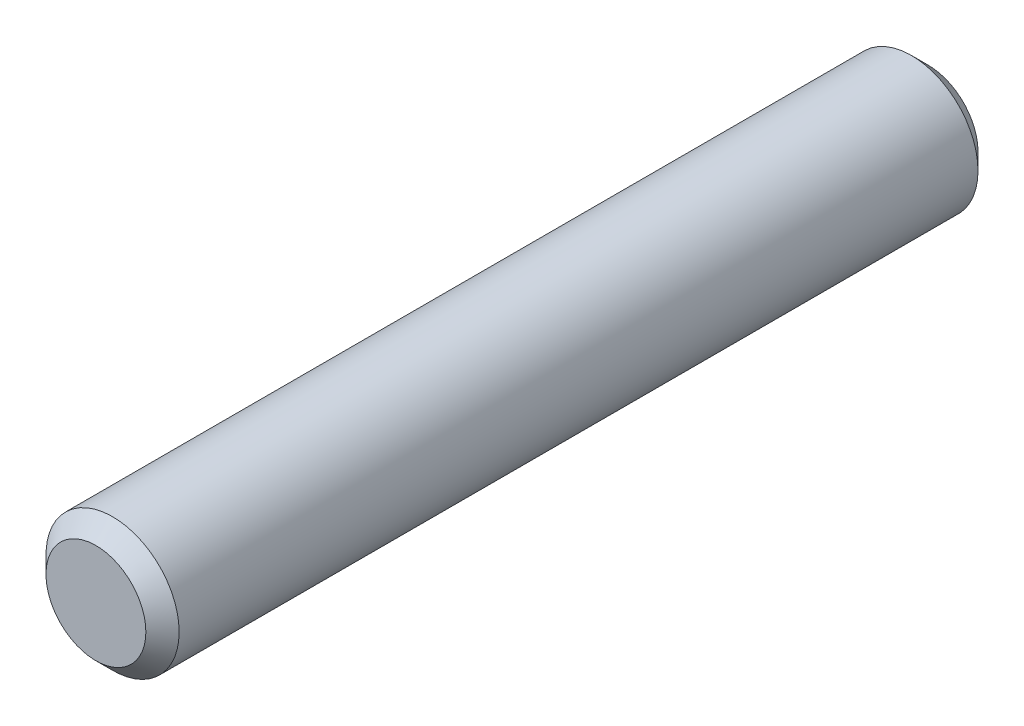
SolidWorks part; units mm, degrees
ref_plane "Front Plane" through (0, 0, 0) normal (0, 0, 1) x (1, 0, 0)
ref_plane "Top Plane" through (0, 0, 0) normal (0, 1, 0) x (1, 0, 0)
ref_plane "Right Plane" through (0, 0, 0) normal (1, 0, 0) x (0, 0, -1)
sketch "Sketch1" plane through (0, 0, 0) normal (0, 0, 1) x (1, 0, 0)
  circle A0 centre (0, 0) radius 4
  dimension "D1" = 8
extrude "Boss-Extrude1" add sketch "Sketch1" along normal blind 50
chamfer "Chamfer1" distance 1 angle 45 2 edges at (4, 0, 50) (4, 0, 0)
